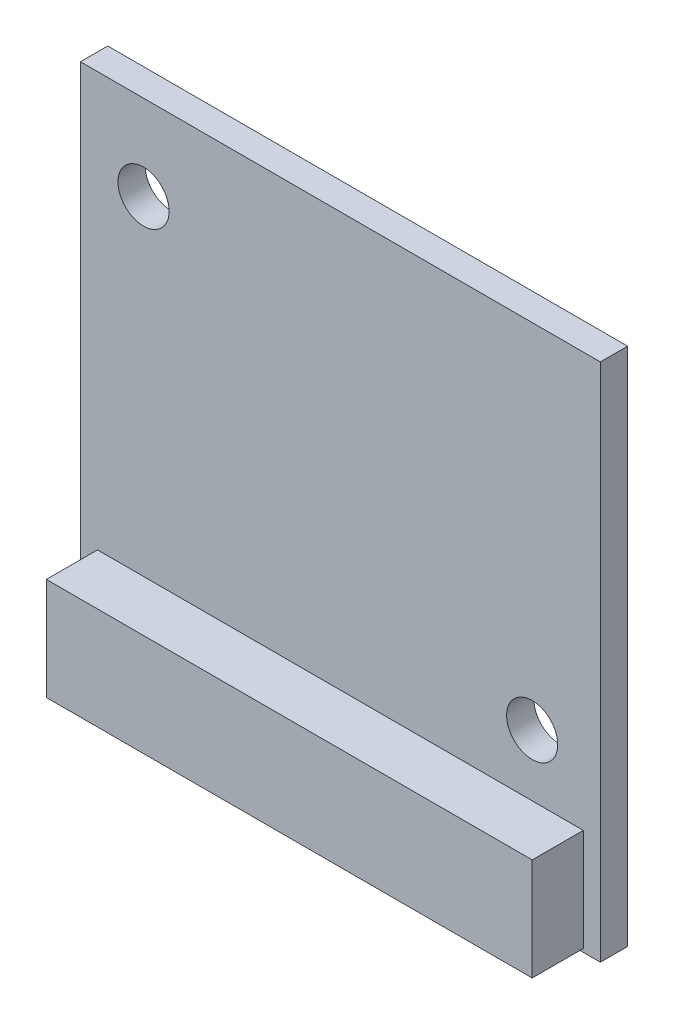
SolidWorks part; units mm, degrees
ref_plane "Płaszczyzna przednia" through (0, 0, 0) normal (0, 0, 1) x (1, 0, 0)
ref_plane "Płaszczyzna górna" through (0, 0, 0) normal (0, 1, 0) x (1, 0, 0)
ref_plane "Płaszczyzna prawa" through (0, 0, 0) normal (1, 0, 0) x (0, 0, -1)
sketch "Sketch1" plane through (0, 0, 0) normal (0, 0, 1) x (1, 0, 0)
  line L1 (0, 0) -> (30.5, 0)
  line L2 (0, 0) -> (0, 30.5)
  line L3 (0, 30.5) -> (30.5, 30.5)
  line L4 (30.5, 0) -> (30.5, 30.5)
  line L5 (0, 0) -> (30.5, 30.5) construction
  line L6 (0, 30.5) -> (30.5, 0) construction
  point P4 (15.25, 15.25)
  dimension "D1" = 30.5
  dimension "D2" = 30.5
extrude "Boss-Extrude1" add sketch "Sketch1" along normal blind 1.6
hole_wizard "Ø3.0mm Dowel Hole1" positions "Sketch2" profile "Sketch3" hole size "Ø3.0" standard "ANSI Metric" end condition up to next
sketch "Sketch2" plane through (0, 0, 1.6) normal (0, 0, 1) x (1, 0, 0)
  line L0 (30.5, 30.5) -> (0, 30.5) construction
  line L1 (0, 30.5) -> (0, 0) construction
  point P0 (3.7, 25.5)
  point P2 (26.5, 9.8)
  dimension "D1" = 5
  dimension "D2" = 3.7
  dimension "D3" = 20.7
  dimension "D4" = 26.5
sketch "Sketch3" plane through (3.7, 25.5, 1.6) normal (1, 0, 0) x (0, -1, 0)
  line L0 (0, 0) -> (0, 1.6)
  line L1 (0, 1.6) -> (1.5, 1.6)
  line L2 (1.5, 1.6) -> (1.5, 0)
  line L5 (1.5, 0) -> (0, 0)
  line L11 (0, -6.35) -> (0, 107.95) construction
  dimension "Thru Hole Dia." = 3
  dimension "Thru Hole Depth" = 1.6
sketch "Sketch4" plane through (0, 0, 1.6) normal (0, 0, 1) x (1, 0, 0)
  line L0 (0, 0) -> (30.5, 0) construction
  line L1 (1, 6.2) -> (29.5, 6.2)
  line L2 (1, 6.2) -> (1, 0.2)
  line L3 (1, 0.2) -> (29.5, 0.2)
  line L4 (29.5, 6.2) -> (29.5, 0.2)
  line L5 (1, 6.2) -> (29.5, 0.2) construction
  line L6 (1, 0.2) -> (29.5, 6.2) construction
  line L7 (0, 30.5) -> (0, 0) construction
  line L8 (30.5, 0) -> (30.5, 30.5) construction
  point P4 (15.25, 3.2)
  dimension "D1" = 0.2
  dimension "D2" = 1
  dimension "D3" = 1
  dimension "D4" = 6
extrude "Boss-Extrude2" add sketch "Sketch4" along normal blind 3
